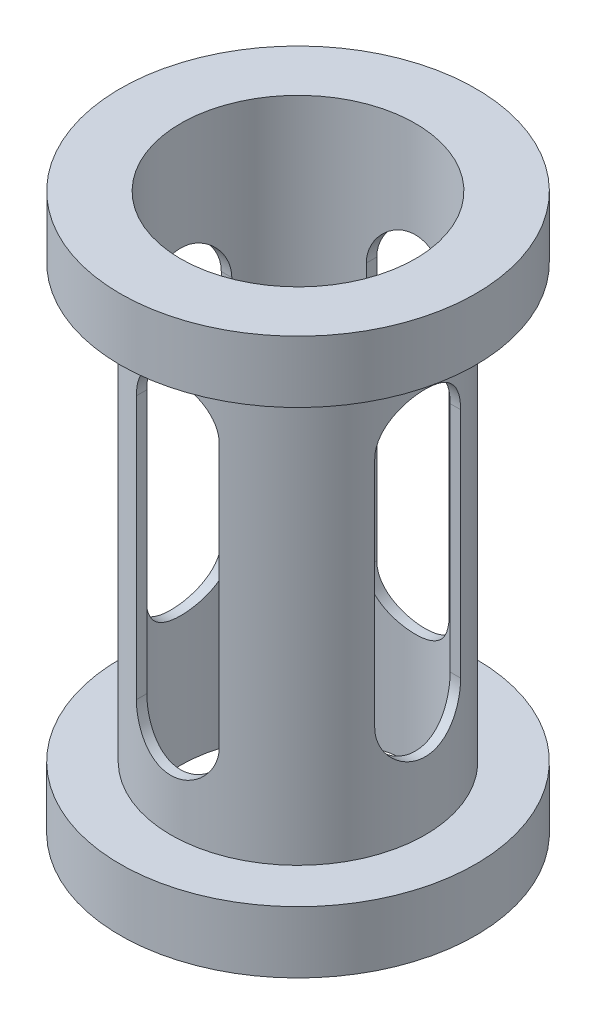
SolidWorks part; units mm, degrees
ref_plane "Plano frontal" through (0, 0, 0) normal (0, 0, 1) x (1, 0, 0)
ref_plane "Plano superior" through (0, 0, 0) normal (0, 1, 0) x (1, 0, 0)
ref_plane "Plano direito" through (0, 0, 0) normal (1, 0, 0) x (0, 0, -1)
sketch "Esboço1" plane through (0, 0, 0) normal (0, 1, 0) x (1, 0, 0)
  circle A0 centre (0, 0) radius 20.5883
extrude "Ressalto-extrusão1" add sketch "Esboço1" along normal blind 70
sketch "Esboço2" plane through (0, 0, 0) normal (0, -1, 0) x (1, 0, 0)
  circle A0 centre (0, 0) radius 28.7819
extrude "Ressalto-extrusão2" add sketch "Esboço2" along normal blind 10
sketch "Esboço4" plane through (0, 70, 0) normal (0, 1, 0) x (1, 0, 0)
  circle A0 centre (0, 0) radius 28.78
  dimension "D1" = 57.56
extrude "Ressalto-extrusão3" add sketch "Esboço4" along normal blind 10
sketch "Esboço5" plane through (0, 80, 0) normal (0, 1, 0) x (1, 0, 0)
  circle A1 centre (0, 0) radius 19
  dimension "D1" = 38
extrude "Corte-extrusão4" cut sketch "Esboço5" against normal up to surface (90 mm away) up to face at (0, -10, -28.7819)
sketch "Esboço6" plane through (0, 0, 0) normal (1, 0, 0) x (0, 0, -1)
  line L0 (0, 0) -> (0, 70) construction
  line L1 (-20.5883, 70) -> (20.5883, 70) construction
  line L2 (0, 55.5585) -> (0, 17.9197) construction
  line L3 (6.9563, 55.5585) -> (6.9563, 17.9197)
  line L4 (-6.9563, 55.5585) -> (-6.9563, 17.9197)
  arc A0 (6.9563, 55.5585) -> (-6.9563, 55.5585) centre (0, 55.5585) ccw
  arc A1 (-6.9563, 17.9197) -> (6.9563, 17.9197) centre (0, 17.9197) ccw
  point P7 (0, 36.7391)
extrude "Corte-extrusão5" cut sketch "Esboço6" against normal through all both and the other way through all
sketch "Esboço7" plane through (0, 0, 0) normal (0, 0, 1) x (1, 0, 0)
  line L0 (0, 0) -> (0, 70) construction
  line L1 (-20.5883, 70) -> (20.5883, 70) construction
  line L2 (0, 57.6702) -> (0, 15.0626) construction
  line L3 (6.7079, 57.6702) -> (6.7079, 15.0626)
  line L4 (-6.7079, 57.6702) -> (-6.7079, 15.0626)
  arc A0 (6.7079, 57.6702) -> (-6.7079, 57.6702) centre (0, 57.6702) ccw
  arc A1 (-6.7079, 15.0626) -> (6.7079, 15.0626) centre (0, 15.0626) ccw
  point P7 (0, 36.3664)
extrude "Corte-extrusão6" cut sketch "Esboço7" against normal through all both and the other way through all
